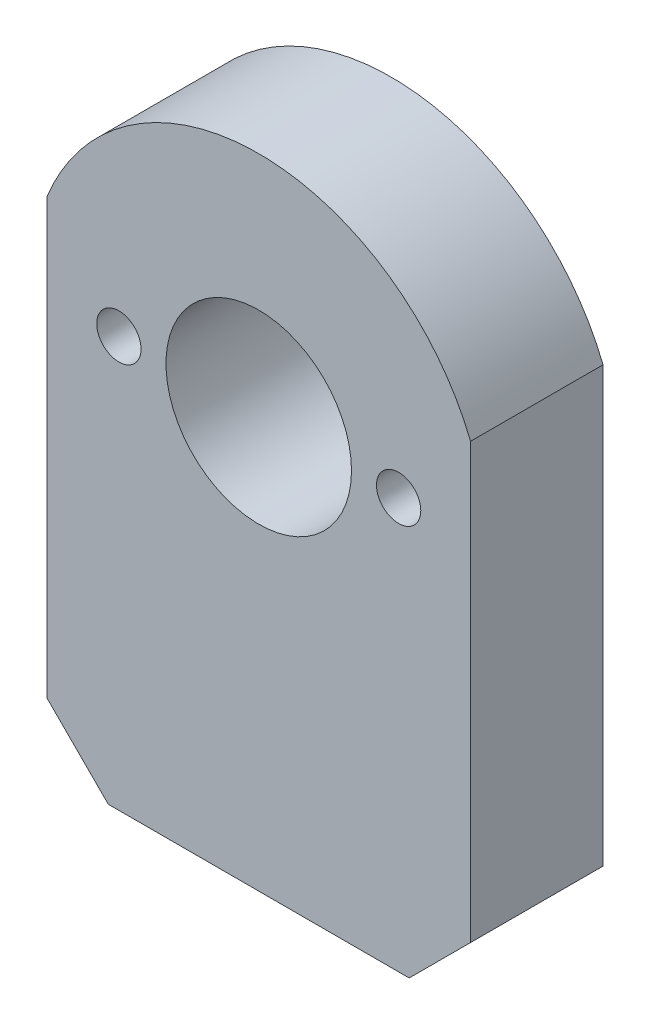
SolidWorks part; units mm, degrees
ref_plane "Front Plane" through (0, 0, 0) normal (0, 0, 1) x (1, 0, 0)
ref_plane "Top Plane" through (0, 0, 0) normal (0, 1, 0) x (1, 0, 0)
ref_plane "Right Plane" through (0, 0, 0) normal (1, 0, 0) x (0, 0, -1)
sketch "Sketch1" plane through (0, 0, 0) normal (0, 0, 1) x (1, 0, 0)
  line L0 (0, 0) -> (20.4377, 0)
  line L1 (20.4377, 0) -> (24.6038, 4.1662)
  line L2 (24.6038, 4.1662) -> (24.6038, 33.6525)
  line L3 (0, 0) -> (-4.1662, 4.1662)
  line L4 (-4.1662, 4.1662) -> (-4.1662, 33.6525)
  line L5 (10.2188, 27.88) -> (-4.1662, 27.88) construction
  line L6 (10.2188, 27.88) -> (24.6038, 27.88) construction
  line L8 (-4.1662, 4.1662) -> (-4.1662, 0) construction
  line L9 (-4.1662, 0) -> (0, 0) construction
  line L10 (24.6038, 4.1662) -> (24.6038, 0) construction
  line L11 (24.6038, 0) -> (20.4377, 0) construction
  arc A0 (-4.1662, 33.6525) -> (24.6038, 33.6525) centre (10.2188, 27.88) cw
  circle A1 centre (10.2188, 27.88) radius 6.3
  point P14 (10.2188, 43.38)
  dimension "D2" = 15.5
  dimension "D3" = 12.6
  dimension "D4" = 43.38
  dimension "D1" = 28.77
extrude "Boss-Extrude1" add sketch "Sketch1" along normal blind 9
ref_plane "Plane2" through (0, 43.38, 0) normal (0, 1, 0) x (1, 0, 0)
sketch "Sketch2" plane through (0, 0, 9) normal (0, 0, 1) x (1, 0, 0)
  line L0 (0.7188, 27.88) -> (10.2188, 27.88) construction
  line L1 (10.2188, 27.88) -> (19.7188, 27.88) construction
  circle A0 centre (10.2188, 27.88) radius 6.3
  circle A1 centre (0.7188, 27.88) radius 1.505
  circle A2 centre (19.7188, 27.88) radius 1.505
  circle A3 centre (10.2188, 27.88) radius 6.3 construction
  dimension "D2" = 3.01
  dimension "D1" = 19
extrude "Cut-Extrude1" cut sketch "Sketch2" against normal up to surface (9 mm away) contours A1 | A2 up to face at (10.2188, 14.2275, 0)
